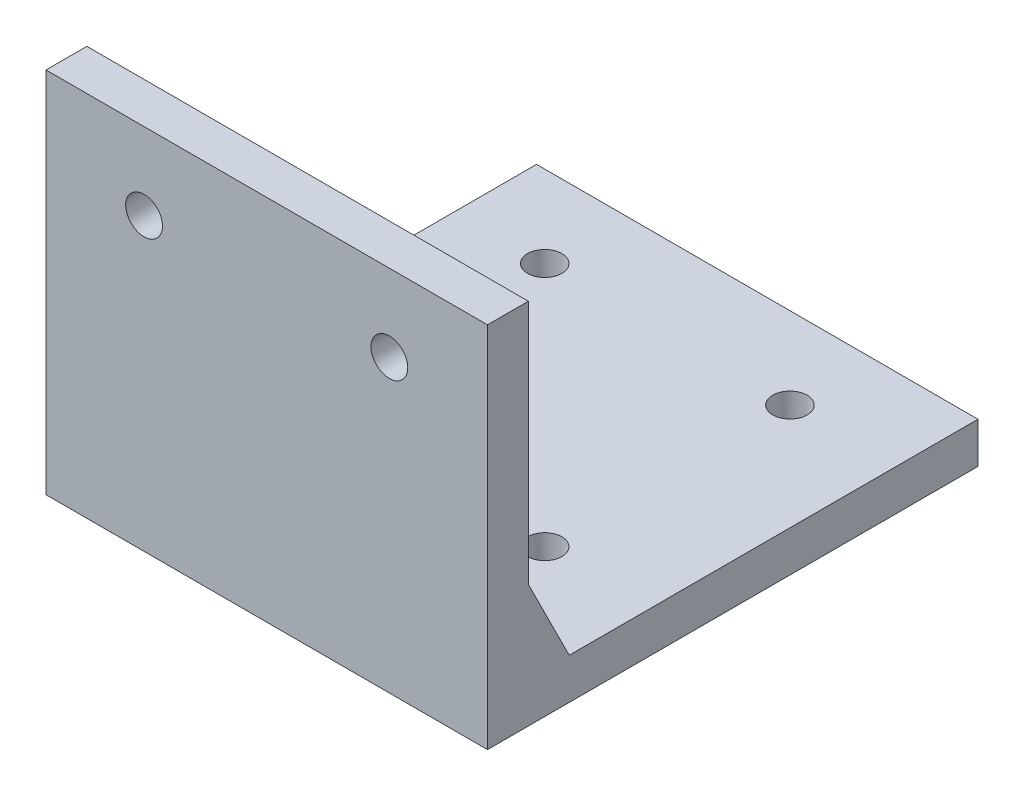
SolidWorks part; units mm, degrees
ref_plane "前视基准面" through (0, 0, 0) normal (0, 0, 1) x (1, 0, 0)
ref_plane "上视基准面" through (0, 0, 0) normal (0, 1, 0) x (1, 0, 0)
ref_plane "右视基准面" through (0, 0, 0) normal (1, 0, 0) x (0, 0, -1)
other "Configuration Table"
sketch "草图1" plane through (0, 0, 0) normal (1, 0, 0) x (0, 0, -1)
  line L1 (-1.1556, -17.9206) -> (58.8444, -17.9206)
  line L2 (-1.1556, -17.9206) -> (-1.1556, 27.0794)
  line L3 (-1.1556, 27.0794) -> (58.8444, 27.0794)
  line L4 (58.8444, -17.9206) -> (58.8444, 27.0794)
  dimension "D1" = 60
  dimension "D2" = 45
extrude "凸台-拉伸2" add sketch "草图1" along normal blind 54 contours L3 L4 L1 L2
sketch "草图4" plane through (54, 0, 0) normal (1, 0, 0) x (0, 0, -1)
  line L0 (3.8444, 27.0794) -> (3.8444, -12.9206)
  line L1 (-1.1556, 27.0794) -> (58.8444, 27.0794) construction
  line L2 (3.8444, -12.9206) -> (58.8444, -12.9206)
  line L3 (58.8444, -17.9206) -> (58.8444, 27.0794) construction
  line L4 (58.8444, -12.9206) -> (58.8444, 27.0794)
  line L5 (58.8444, 27.0794) -> (3.8444, 27.0794)
  dimension "D1" = 40
  dimension "D2" = 55
extrude "切除-拉伸3" cut sketch "草图4" against normal blind 54
sketch "草图5" plane through (0, 0, -3.8444) normal (0, 0, -1) x (-1, 0, 0)
  line L0 (-54, 27.0794) -> (-54, -12.9206) construction
  circle A0 centre (-42, 17.6532) radius 2.25
  circle A1 centre (-12, 17.6532) radius 2.25
  dimension "D1" = 4.5
  dimension "D2" = 4.5
  dimension "D3" = 30
  dimension "D4" = 12
extrude "切除-拉伸4" cut sketch "草图5" against normal mid plane 54
sketch "草图6" plane through (0, -12.9206, 0) normal (0, 1, 0) x (1, 0, 0)
  line L0 (0, 3.8444) -> (0, 58.8444) construction
  line L6 (0, 58.8444) -> (54, 58.8444) construction
  circle A0 centre (11, 48.8444) radius 2.1
  circle A1 centre (41, 48.8444) radius 2.1
  circle A2 centre (11, 18.8444) radius 2.1
  circle A4 centre (41, 18.8444) radius 2.1
  dimension "D1" = 4.2
  dimension "D2" = 4.2
  dimension "D3" = 4.2
  dimension "D4" = 4.2
  dimension "D7" = 30
  dimension "D10" = 10
  dimension "D5" = 30
  dimension "D6" = 30
  dimension "D8" = 11
extrude "切除-拉伸5" cut sketch "草图6" against normal mid plane 54
sketch "草图7" plane through (54, 0, 0) normal (1, 0, 0) x (0, 0, -1)
  line L0 (3.8444, -2.9206) -> (8.8444, -12.9206)
  line L1 (3.8444, 27.0794) -> (3.8444, -12.9206) construction
  line L2 (3.8444, -12.9206) -> (58.8444, -12.9206) construction
  line L3 (8.8444, -12.9206) -> (3.8444, -12.9206)
  line L4 (3.8444, -12.9206) -> (3.8444, -2.9206)
  dimension "D1" = 10
  dimension "D2" = 5
extrude "凸台-拉伸3" add sketch "草图7" against normal blind 54
